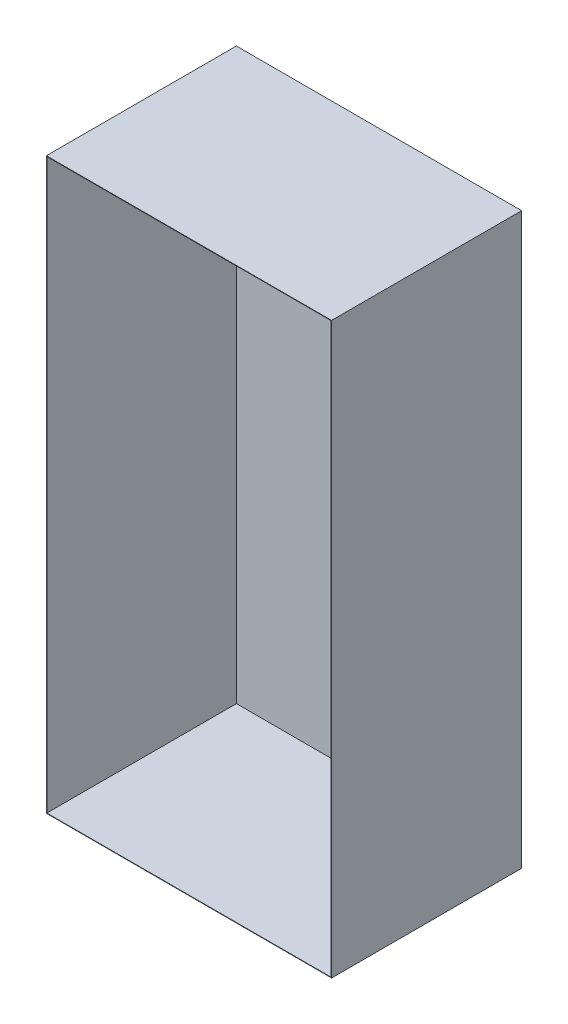
SolidWorks part; units mm, degrees
material "6061-T4 (SS)"
ref_plane "Front Plane" through (0, 0, 0) normal (0, 0, 1) x (1, 0, 0)
ref_plane "Top Plane" through (0, 0, 0) normal (0, 1, 0) x (1, 0, 0)
ref_plane "Right Plane" through (0, 0, 0) normal (1, 0, 0) x (0, 0, -1)
sketch "Front" plane through (0, 0, 0) normal (0, 0, 1) x (1, 0, 0)
  line L1 (-76.454, -152.654) -> (76.454, -152.654)
  line L2 (-76.454, -152.654) -> (-76.454, 152.654)
  line L3 (-76.454, 152.654) -> (76.454, 152.654)
  line L4 (76.454, -152.654) -> (76.454, 152.654)
  line L5 (-76.454, -152.654) -> (76.454, 152.654) construction
  line L6 (-76.454, 152.654) -> (76.454, -152.654) construction
  point P0 (0, 0)
  dimension "D1" = 152.908
  dimension "D2" = 305.308
extrude "Boss-Extrude1" add sketch "Front" along normal blind 101.854
sketch "Sketch3" plane through (0, 0, 101.854) normal (0, 0, 1) x (1, 0, 0)
  line L1 (-76.2, -152.4) -> (76.2, -152.4)
  line L2 (-76.2, -152.4) -> (-76.2, 152.4)
  line L3 (-76.2, 152.4) -> (76.2, 152.4)
  line L4 (76.2, -152.4) -> (76.2, 152.4)
  line L5 (-76.2, -152.4) -> (76.2, 152.4) construction
  line L6 (-76.2, 152.4) -> (76.2, -152.4) construction
  point P0 (0, 0)
  dimension "D1" = 152.4
  dimension "D2" = 304.8
extrude "Cut-Extrude1" cut sketch "Sketch3" against normal blind 101.6
sketch "Sketch4" plane through (0, 0, 0.254) normal (0, 0, 1) x (1, 0, 0)
  line L0 (76.2, -152.4) -> (76.2, 152.4) construction
  line L1 (48.6981, 105.3592) -> (56.3181, 105.3592)
  line L2 (48.6981, 105.3592) -> (48.6981, 134.366)
  line L3 (48.6981, 134.366) -> (56.3181, 134.366)
  line L4 (56.3181, 105.3592) -> (56.3181, 134.366)
  line L5 (48.6981, 105.3592) -> (56.3181, 134.366) construction
  line L6 (48.6981, 134.366) -> (56.3181, 105.3592) construction
  line L7 (76.2, 152.4) -> (-76.2, 152.4) construction
  line L8 (-48.6981, 105.3592) -> (-48.6981, 134.366)
  line L9 (-56.3181, 105.3592) -> (-56.3181, 134.366)
  line L10 (-48.6981, 65.6844) -> (-48.6981, 94.6912)
  line L11 (-56.3181, 65.6844) -> (-56.3181, 94.6912)
  line L12 (-48.6981, 26.0096) -> (-48.6981, 55.0164)
  line L13 (-56.3181, 26.0096) -> (-56.3181, 55.0164)
  line L14 (-48.6981, -13.6652) -> (-48.6981, 15.3416)
  line L15 (-56.3181, -13.6652) -> (-56.3181, 15.3416)
  line L16 (-48.6981, -53.34) -> (-48.6981, -24.3332)
  line L17 (-56.3181, -53.34) -> (-56.3181, -24.3332)
  line L18 (-48.6981, -93.0148) -> (-48.6981, -64.008)
  line L19 (-56.3181, -93.0148) -> (-56.3181, -64.008)
  line L20 (56.3182, 65.6844) -> (56.3182, 94.6912)
  line L21 (48.6982, 65.6844) -> (48.6982, 94.6912)
  line L22 (56.3182, 26.0096) -> (56.3182, 55.0164)
  line L23 (48.6982, 26.0096) -> (48.6982, 55.0164)
  line L24 (56.3182, -13.6652) -> (56.3182, 15.3416)
  line L25 (48.6982, -13.6652) -> (48.6982, 15.3416)
  line L26 (56.3182, -53.34) -> (56.3182, -24.3332)
  line L27 (48.6982, -53.34) -> (48.6982, -24.3332)
  line L28 (56.3182, -93.0148) -> (56.3182, -64.008)
  line L29 (48.6982, -93.0148) -> (48.6982, -64.008)
  arc A0 (56.3181, 134.366) -> (48.6981, 134.366) centre (52.5081, 134.366) ccw
  arc A1 (48.6981, 105.3592) -> (56.3181, 105.3592) centre (52.5081, 105.3592) ccw
  arc A2 (-56.3181, 105.3592) -> (-48.6981, 105.3592) centre (-52.5081, 105.3592) ccw
  arc A3 (-48.6981, 134.366) -> (-56.3181, 134.366) centre (-52.5081, 134.366) ccw
  arc A4 (-56.3181, 65.6844) -> (-48.6981, 65.6844) centre (-52.5081, 65.6844) ccw
  arc A5 (-48.6981, 94.6912) -> (-56.3181, 94.6912) centre (-52.5081, 94.6912) ccw
  arc A6 (-56.3181, 26.0096) -> (-48.6981, 26.0096) centre (-52.5081, 26.0096) ccw
  arc A7 (-48.6981, 55.0164) -> (-56.3181, 55.0164) centre (-52.5081, 55.0164) ccw
  arc A8 (-56.3181, -13.6652) -> (-48.6981, -13.6652) centre (-52.5081, -13.6652) ccw
  arc A9 (-48.6981, 15.3416) -> (-56.3181, 15.3416) centre (-52.5081, 15.3416) ccw
  arc A10 (-56.3181, -53.34) -> (-48.6981, -53.34) centre (-52.5081, -53.34) ccw
  arc A11 (-48.6981, -24.3332) -> (-56.3181, -24.3332) centre (-52.5081, -24.3332) ccw
  arc A12 (-56.3181, -93.0148) -> (-48.6981, -93.0148) centre (-52.5081, -93.0148) ccw
  arc A13 (-48.6981, -64.008) -> (-56.3181, -64.008) centre (-52.5081, -64.008) ccw
  arc A14 (48.6982, 65.6844) -> (56.3182, 65.6844) centre (52.5082, 65.6844) ccw
  arc A15 (56.3182, 94.6912) -> (48.6982, 94.6912) centre (52.5082, 94.6912) ccw
  arc A16 (48.6982, 26.0096) -> (56.3182, 26.0096) centre (52.5082, 26.0096) ccw
  arc A17 (56.3182, 55.0164) -> (48.6982, 55.0164) centre (52.5082, 55.0164) ccw
  arc A18 (48.6982, -13.6652) -> (56.3182, -13.6652) centre (52.5082, -13.6652) ccw
  arc A19 (56.3182, 15.3416) -> (48.6982, 15.3416) centre (52.5082, 15.3416) ccw
  arc A20 (48.6982, -53.34) -> (56.3182, -53.34) centre (52.5082, -53.34) ccw
  arc A21 (56.3182, -24.3332) -> (48.6982, -24.3332) centre (52.5082, -24.3332) ccw
  arc A22 (48.6982, -93.0148) -> (56.3182, -93.0148) centre (52.5082, -93.0148) ccw
  arc A23 (56.3182, -64.008) -> (48.6982, -64.008) centre (52.5082, -64.008) ccw
  point P0 (52.5082, 119.8626)
  dimension "D1" = 23.6918
  dimension "D2" = 32.5374
  dimension "D3" = 7.62
  dimension "D4" = 29.0068
  dimension "D5" = 2
  dimension "D6" = 6
extrude "Cut-Extrude3" [suppressed] cut sketch "Sketch4" against normal blind 2.54 contours L3 A0 | L1 L4 L3 L2 | L1 A1 | L20 A15 L21 A14 | L22 A17 L23 A16 | L24 A19 L25 A18 | L26 A21 L27 A20 | L14 A9 L15 A8 | L16 A11 L17 A10 | L12 A7 L13 A6 | L8 A3 L9 A2 | L18 A13 L19 A12 | L10 A5 L11 A4 | L28 A23 L29 A22
